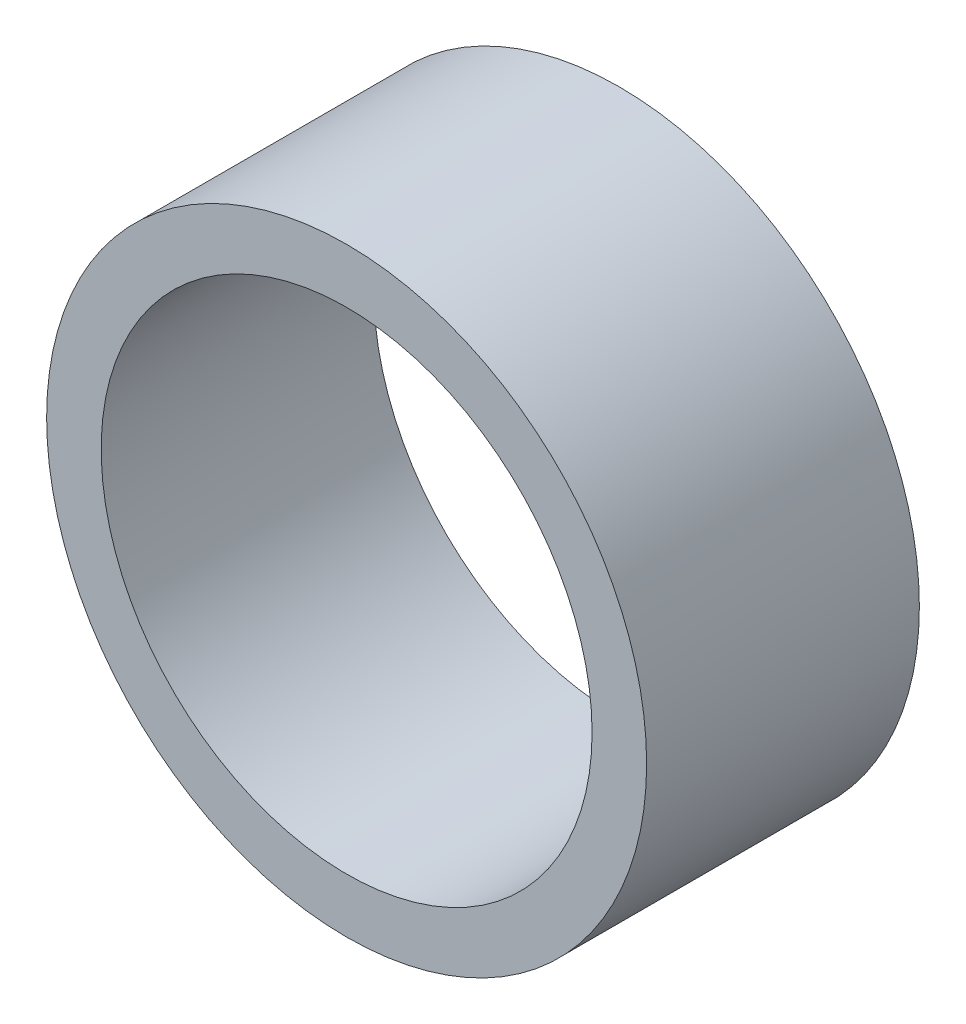
SolidWorks part; units mm, degrees
ref_plane "前视基准面" through (0, 0, 0) normal (0, 0, 1) x (1, 0, 0)
ref_plane "上视基准面" through (0, 0, 0) normal (0, 1, 0) x (1, 0, 0)
ref_plane "右视基准面" through (0, 0, 0) normal (1, 0, 0) x (0, 0, -1)
sketch "草图1" plane through (0, 0, 0) normal (0, 0, 1) x (1, 0, 0)
  circle A0 centre (0, 0) radius 5.5
  circle A1 centre (0, 0) radius 4.5
  dimension "D1" = 11
  dimension "D2" = 9
extrude "凸台-拉伸1" add sketch "草图1" along normal blind 5
